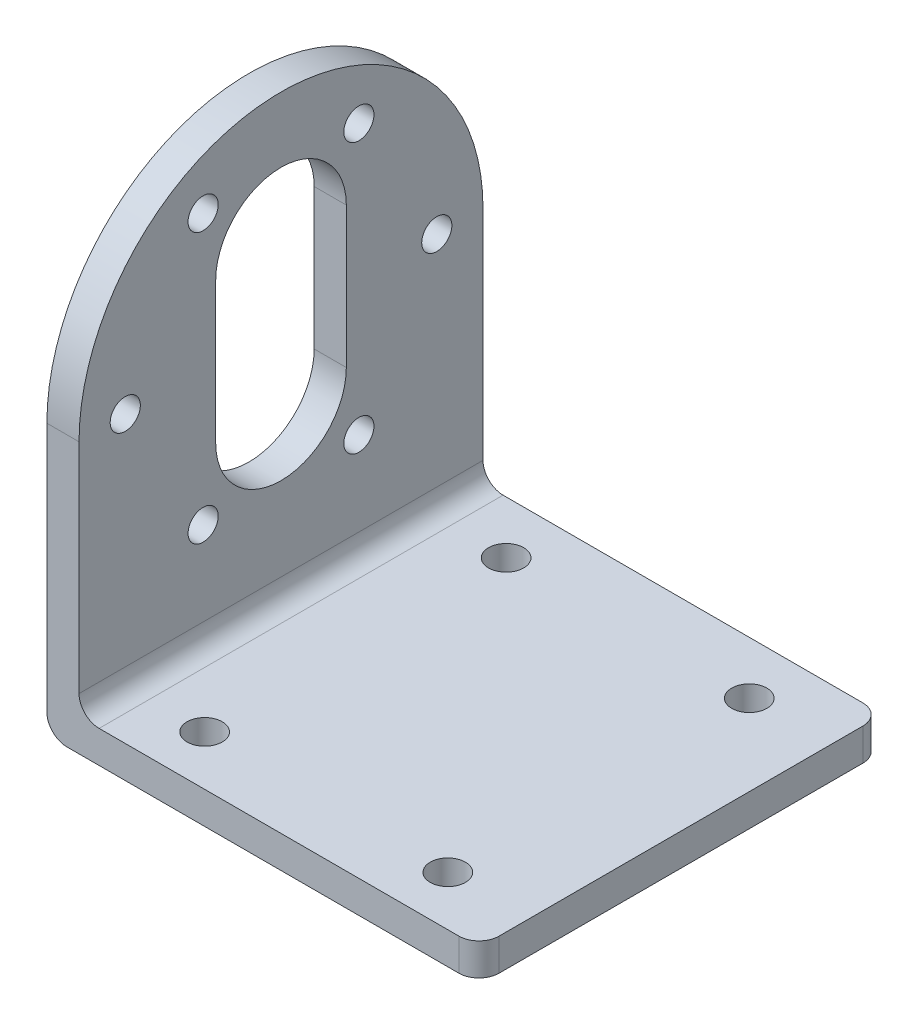
SolidWorks part; units mm, degrees
ref_plane "前视基准面" through (0, 0, 0) normal (0, 0, 1) x (1, 0, 0)
ref_plane "上视基准面" through (0, 0, 0) normal (0, 1, 0) x (1, 0, 0)
ref_plane "右视基准面" through (0, 0, 0) normal (1, 0, 0) x (0, 0, -1)
sketch "草图1" plane through (0, 0, 0) normal (0, 1, 0) x (1, 0, 0)
  line L1 (21.5, -20.1) -> (-21.5, -20.1)
  line L2 (21.5, -20.1) -> (21.5, 20.1)
  line L3 (21.5, 20.1) -> (-21.5, 20.1)
  line L4 (-21.5, -20.1) -> (-21.5, 20.1)
  point P0 (0, 0)
  dimension "D1" = 43
  dimension "D2" = 40.2
extrude "凸台-拉伸1" add sketch "草图1" along normal blind 3.2
sketch "草图2" plane through (0, 3.2, 0) normal (0, 1, 0) x (1, 0, 0)
  line L0 (-18.3, 20.1) -> (-18.3, -20.1)
  line L1 (21.5, 20.1) -> (-21.5, 20.1) construction
  line L2 (-21.5, -20.1) -> (21.5, -20.1) construction
  line L3 (-21.5, 20.1) -> (-21.5, -20.1) construction
  line L4 (-21.5, -20.1) -> (21.5, -20.1)
  line L5 (21.5, 20.1) -> (-21.5, 20.1)
  line L6 (-21.5, 20.1) -> (-21.5, -20.1)
  line M2 (-21.5, 20.1) -> (-21.5, -20.1)
  line M3 (-21.5, -20.1) -> (21.5, -20.1)
  line M5 (21.5, 20.1) -> (-21.5, 20.1)
  dimension "D1" = 3.2
extrude "凸台-拉伸2" add sketch "草图2" along normal blind 43.8 contours L0 M5 M2 M3
sketch "草图3" plane through (-21.5, 0, 0) normal (-1, 0, 0) x (0, 0, 1)
  line L0 (-20.1, 0) -> (20.1, 0) construction
  line L1 (-6.5, 34) -> (-6.5, 20)
  line L2 (6.5, 34) -> (6.5, 20)
  arc A0 (6.5, 34) -> (-6.5, 34) centre (0, 34) ccw
  arc A1 (-6.5, 20) -> (6.5, 20) centre (0, 20) ccw
  circle A2 centre (0, 27) radius 15.5 construction
  circle A3 centre (-15.5, 27) radius 1.5
  circle A4 centre (-7.75, 40.4234) radius 1.5
  circle A5 centre (7.75, 40.4234) radius 1.5
  circle A6 centre (15.5, 27) radius 1.5
  circle A7 centre (7.75, 13.5766) radius 1.5
  circle A8 centre (-7.75, 13.5766) radius 1.5
  dimension "D1" = 13
  dimension "D2" = 13
  dimension "D5" = 31
  dimension "D6" = 3
  dimension "D3" = 20
  dimension "D4" = 34
  dimension "D7" = 6
extrude "切除-拉伸1" cut sketch "草图3" against normal blind 43.8
sketch "草图4" plane through (-21.5, 0, 0) normal (-1, 0, 0) x (0, 0, 1)
  line L1 (-20.1, 47) -> (20.1, 47) construction
  line L6 (-20.1, 0) -> (20.1, 0)
  line L7 (20.1, 0) -> (20.1, 47)
  line L8 (20.1, 47) -> (-20.1, 47)
  line L9 (-20.1, 47) -> (-20.1, 0)
  line L11 (20.1, 26.9) -> (20.1, 47)
  line L12 (20.1, 47) -> (-20.1, 47)
  line L13 (-20.1, 47) -> (-20.1, 26.9)
  arc A0 (20.1, 26.9) -> (-20.1, 26.9) centre (0, 26.9) ccw
  line M17 (20.1, 0) -> (20.1, 47)
  line M18 (20.1, 47) -> (-20.1, 47)
  line M19 (-20.1, 47) -> (-20.1, 0)
  dimension "D1" = 40.2
  dimension "D2" = 0
extrude "切除-拉伸2" cut sketch "草图4" against normal blind 43.8 contours A0 L12 M19 | A0 M17 M18
fillet "圆角1" radius 2 1 edges at (-21.5, 0, 0)
fillet "圆角2" radius 2 1 edges at (-18.3, 3.2, 0)
sketch "草图5" plane through (0, 3.2, 0) normal (0, 1, 0) x (1, 0, 0)
  line L0 (21.5, -20.1) -> (21.5, 20.1) construction
  line L1 (21.5, 20.1) -> (-16.3, 20.1) construction
  circle A0 centre (13.45, 14.85) radius 1.75
  circle A1 centre (13.45, -15.15) radius 1.75
  circle A2 centre (-10.75, -15.15) radius 1.75
  circle A3 centre (-10.75, 14.85) radius 1.75
  dimension "D1" = 3.5
  dimension "D2" = 3.5
  dimension "D4" = 5.25
  dimension "D5" = 30
  dimension "D6" = 3.5
  dimension "D7" = 3.5
  dimension "D9" = 8.05
  dimension "D3" = 8.05
  dimension "D8" = 24.2
extrude "切除-拉伸3" cut sketch "草图5" against normal blind 43.8
fillet "圆角3" radius 2 2 edges at (21.5, 1.6, -20.1) (21.5, 1.6, 20.1)
